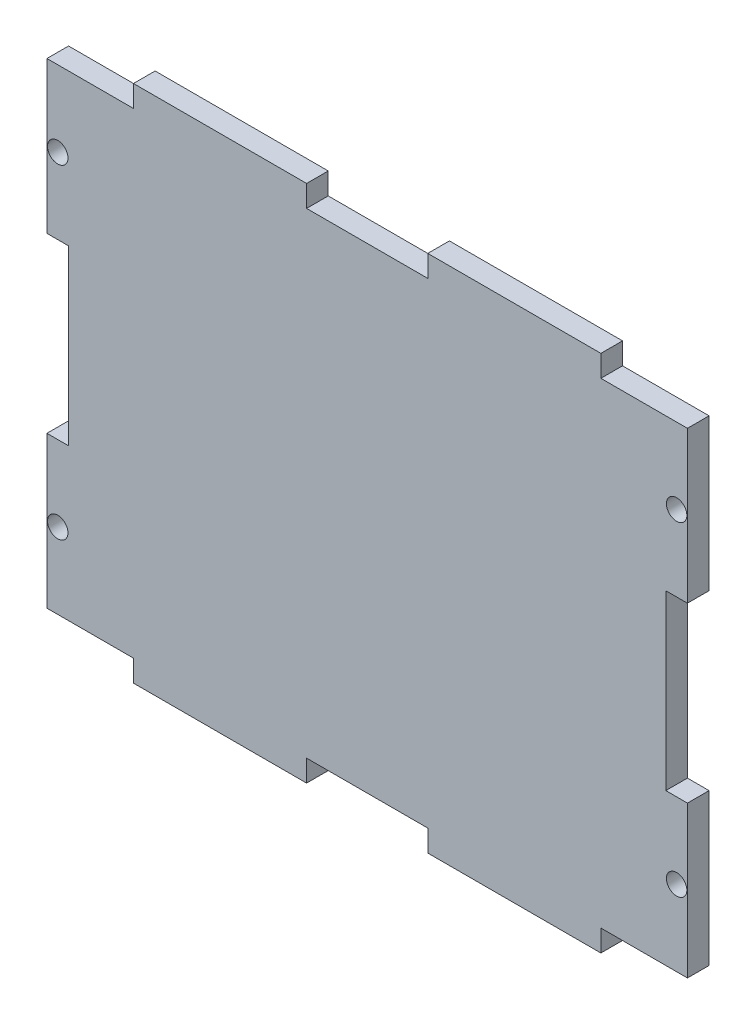
SolidWorks part; units mm, degrees
ref_plane "Front Plane" through (0, 0, 0) normal (0, 0, 1) x (1, 0, 0)
ref_plane "Top Plane" through (0, 0, 0) normal (0, 1, 0) x (1, 0, 0)
ref_plane "Right Plane" through (0, 0, 0) normal (1, 0, 0) x (0, 0, -1)
sketch "Sketch1" plane through (0, 0, 0) normal (0, 0, 1) x (1, 0, 0)
  line L1 (-46.99, -38.1) -> (46.99, -38.1)
  line L2 (-46.99, -38.1) -> (-46.99, 38.1)
  line L3 (-46.99, 38.1) -> (46.99, 38.1)
  line L4 (46.99, -38.1) -> (46.99, 38.1)
  line L5 (-46.99, -38.1) -> (46.99, 38.1) construction
  line L6 (-46.99, 38.1) -> (46.99, -38.1) construction
  point P0 (0, 0)
  dimension "D1" = 93.98
  dimension "D2" = 76.2
extrude "Boss-Extrude1" add sketch "Sketch1" along normal blind 3.175
sketch "Sketch2" plane through (0, 0, 3.175) normal (0, 0, 1) x (1, 0, 0)
  line L0 (-46.99, -38.1) -> (46.99, -38.1) construction
  line L1 (-34.29, -38.1) -> (-8.89, -38.1) construction
  line L2 (-34.29, -38.1) -> (-34.29, -34.925) construction
  line L3 (-34.29, -34.925) -> (-8.89, -34.925) construction
  line L4 (-8.89, -38.1) -> (-8.89, -34.925) construction
  line L5 (-46.99, 38.1) -> (-46.99, -38.1) construction
  line L6 (8.89, -38.1) -> (34.29, -38.1) construction
  line L7 (8.89, -38.1) -> (8.89, -34.925) construction
  line L8 (8.89, -34.925) -> (34.29, -34.925) construction
  line L9 (34.29, -38.1) -> (34.29, -34.925) construction
  line L10 (-46.99, 0) -> (46.99, 0) construction
  line L11 (46.99, -38.1) -> (46.99, 38.1) construction
  line L12 (34.29, 38.1) -> (34.29, 34.925) construction
  line L13 (8.89, 34.925) -> (34.29, 34.925) construction
  line L14 (8.89, 38.1) -> (8.89, 34.925) construction
  line L15 (8.89, 38.1) -> (34.29, 38.1) construction
  line L16 (-8.89, 38.1) -> (-8.89, 34.925) construction
  line L17 (-34.29, 34.925) -> (-8.89, 34.925) construction
  line L18 (-34.29, 38.1) -> (-34.29, 34.925) construction
  line L19 (-34.29, 38.1) -> (-8.89, 38.1) construction
  line L20 (46.99, 38.1) -> (46.99, 34.925)
  line L21 (-46.99, -38.1) -> (-34.29, -38.1)
  line L22 (-46.99, -38.1) -> (-46.99, -34.925)
  line L23 (-46.99, -34.925) -> (-34.29, -34.925)
  line L24 (-34.29, -38.1) -> (-34.29, -34.925)
  line L25 (-8.89, -38.1) -> (8.89, -38.1)
  line L26 (-8.89, -38.1) -> (-8.89, -34.925)
  line L27 (-8.89, -34.925) -> (8.89, -34.925)
  line L28 (8.89, -38.1) -> (8.89, -34.925)
  line L29 (34.29, -38.1) -> (46.99, -38.1)
  line L30 (34.29, -38.1) -> (34.29, -34.925)
  line L31 (34.29, -34.925) -> (46.99, -34.925)
  line L32 (46.99, -38.1) -> (46.99, -34.925)
  line L33 (34.29, 34.925) -> (46.99, 34.925)
  line L34 (34.29, 38.1) -> (34.29, 34.925)
  line L35 (34.29, 38.1) -> (46.99, 38.1)
  line L36 (8.89, 38.1) -> (8.89, 34.925)
  line L37 (-8.89, 34.925) -> (8.89, 34.925)
  line L38 (-8.89, 38.1) -> (-8.89, 34.925)
  line L39 (-8.89, 38.1) -> (8.89, 38.1)
  line L40 (-34.29, 38.1) -> (-34.29, 34.925)
  line L41 (-46.99, 34.925) -> (-34.29, 34.925)
  line L42 (-46.99, 38.1) -> (-46.99, 34.925)
  line L43 (-46.99, 38.1) -> (-34.29, 38.1)
  dimension "D1" = 17.78
  dimension "D2" = 12.7
  dimension "D3" = 25.4
  dimension "D4" = 3.175
extrude "Cut-Extrude1" cut sketch "Sketch2" against normal through all
sketch "Sketch3" plane through (0, 0, 0) normal (0, 0, -1) x (-1, 0, 0)
  line L1 (0, 34.925) -> (0, -34.925) construction
  line L2 (-43.815, 12.7) -> (-46.99, 12.7) construction
  line L3 (-43.815, 12.7) -> (-43.815, 34.925) construction
  line L4 (-43.815, 34.925) -> (-46.99, 34.925) construction
  line L6 (-46.99, 12.7) -> (-46.99, 34.925) construction
  line L7 (-43.815, -12.7) -> (-46.99, -12.7) construction
  line L8 (-43.815, -12.7) -> (-43.815, -34.925) construction
  line L9 (-43.815, -34.925) -> (-46.99, -34.925) construction
  line L10 (-46.99, -12.7) -> (-46.99, -34.925) construction
  line L11 (8.89, 34.925) -> (-8.89, 34.925) construction
  line L12 (-8.89, -34.925) -> (8.89, -34.925) construction
  line L13 (46.99, -12.7) -> (46.99, -34.925) construction
  line L14 (43.815, -34.925) -> (46.99, -34.925) construction
  line L17 (43.815, -12.7) -> (43.815, -34.925) construction
  line L18 (43.815, -12.7) -> (46.99, -12.7) construction
  line L19 (46.99, 12.7) -> (46.99, 34.925) construction
  line L20 (43.815, 34.925) -> (46.99, 34.925) construction
  line L21 (43.815, 12.7) -> (43.815, 34.925) construction
  line L22 (43.815, 12.7) -> (46.99, 12.7) construction
  line L24 (-46.99, 12.7) -> (-43.815, 12.7)
  line L25 (-46.99, 12.7) -> (-46.99, -12.7)
  line L26 (-46.99, -12.7) -> (-43.815, -12.7)
  line L27 (-43.815, 12.7) -> (-43.815, -12.7)
  line L28 (43.815, -12.7) -> (46.99, -12.7)
  line L29 (43.815, -12.7) -> (43.815, 12.7)
  line L30 (43.815, 12.7) -> (46.99, 12.7)
  line L31 (46.99, -12.7) -> (46.99, 12.7)
extrude "Cut-Extrude2" cut sketch "Sketch3" against normal through all
sketch "Sketch4" plane through (0, 0, 0) normal (0, 0, -1) x (-1, 0, 0)
  line L0 (-45.4025, 12.7) -> (-45.4025, 34.925) construction
  line L1 (-43.815, 12.7) -> (-46.99, 12.7) construction
  line L2 (-34.29, 34.925) -> (-46.99, 34.925) construction
  line L3 (-43.815, 0) -> (43.815, 0) construction
  line L4 (-43.815, -12.7) -> (-43.815, 12.7) construction
  line L5 (43.815, 12.7) -> (43.815, -12.7) construction
  line L6 (-45.4025, -12.7) -> (-45.4025, -34.925) construction
  line L7 (0, -34.925) -> (0, 34.925) construction
  line L8 (-8.89, -34.925) -> (8.89, -34.925) construction
  line L9 (8.89, 34.925) -> (-8.89, 34.925) construction
  line L10 (45.4025, -12.7) -> (45.4025, -34.925) construction
  line L11 (45.4025, 12.7) -> (45.4025, 34.925) construction
  circle A0 centre (-45.4025, 23.8125) radius 1.5
  circle A1 centre (-45.4025, -23.8125) radius 1.5
  circle A2 centre (45.4025, -23.8125) radius 1.5
  circle A3 centre (45.4025, 23.8125) radius 1.5
  dimension "D1" = 3
extrude "Cut-Extrude3" cut sketch "Sketch4" against normal through all
